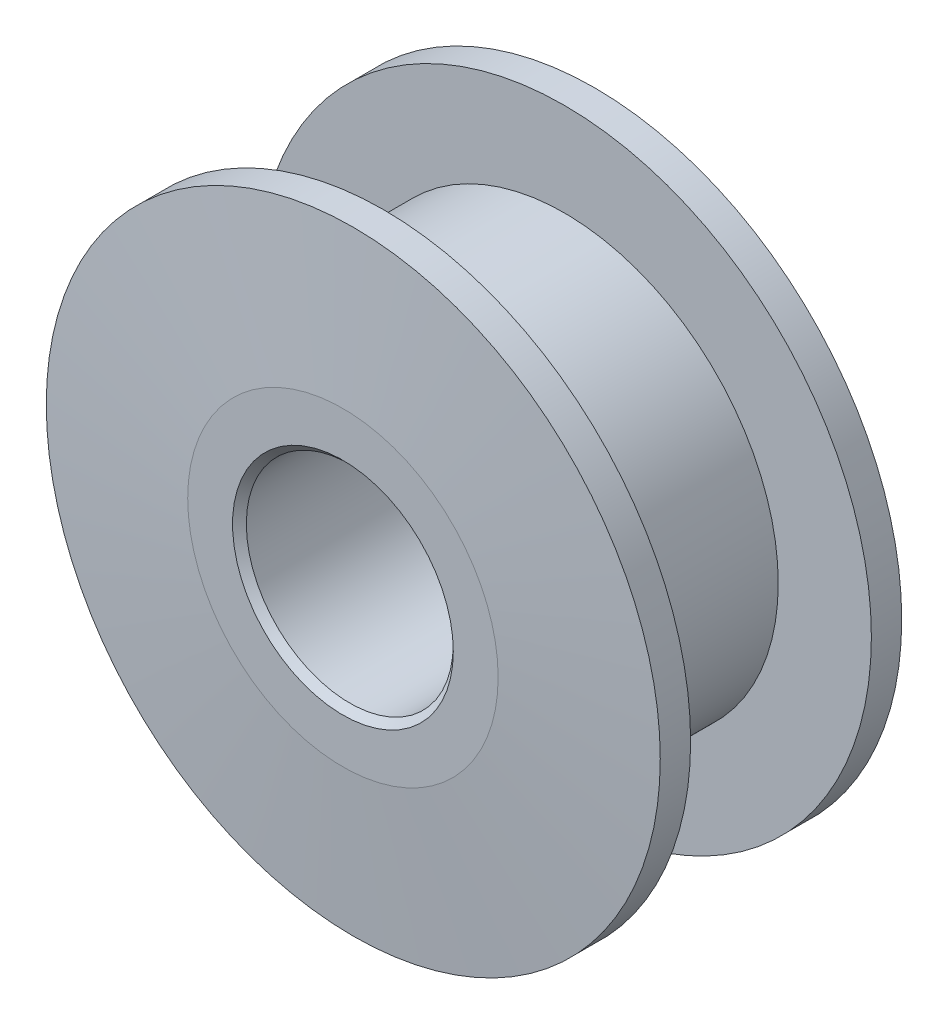
SolidWorks part; units mm, degrees
material "7075-T6，板材(SS)"
ref_plane "前视基准面" through (0, 0, 0) normal (0, 0, 1) x (1, 0, 0)
ref_plane "上视基准面" through (0, 0, 0) normal (0, 1, 0) x (1, 0, 0)
ref_plane "右视基准面" through (0, 0, 0) normal (1, 0, 0) x (0, 0, -1)
sketch "草图1" plane through (0, 0, 0) normal (0, 0, 1) x (1, 0, 0)
  circle A0 centre (0, 0) radius 4.45
  dimension "D1" = 8.9
extrude "拉伸1" add sketch "草图1" along normal mid plane 3.8
sketch "草图2" plane through (0, 0, 0) normal (0, 0, 1) x (1, 0, 0)
  circle A0 centre (0, 0) radius 4.45 construction
  circle A1 centre (0, 0) radius 4.45
  circle A2 centre (0, 0) radius 3.1
  dimension "D1" = 6.2
extrude "拉伸2" cut sketch "草图2" against normal mid plane 2.62
sketch "草图3" plane through (0, 0, 1.9) normal (0, 0, 1) x (1, 0, 0)
  circle A0 centre (0, 0) radius 1
  dimension "D1" = 2
extrude "拉伸3" cut sketch "草图3" against normal up to surface (3.8 mm away) up to face at (4.45, 0, -1.9)
chamfer "倒角1" distance 0.25 angle 45 2 edges at (1, 0, -1.9) (1, 0, 1.9)
chamfer "倒角2" distance 2 distance2 0.15 1 edges at (4.45, 0, -1.9)
chamfer "倒角3" distance 0.15 distance2 2.2 1 edges at (4.45, 0, 1.9)
sketch "草图4" plane through (0, 0, -1.9) normal (0, 0, -1) x (-1, 0, 0)
  circle A0 centre (0, 0) radius 1.5
extrude "切除-拉伸1" cut sketch "草图4" against normal blind 10
chamfer "倒角4" distance 0.1 angle 45 2 edges at (1.5, 0, 1.9) (-1.5, 0, -1.9)
